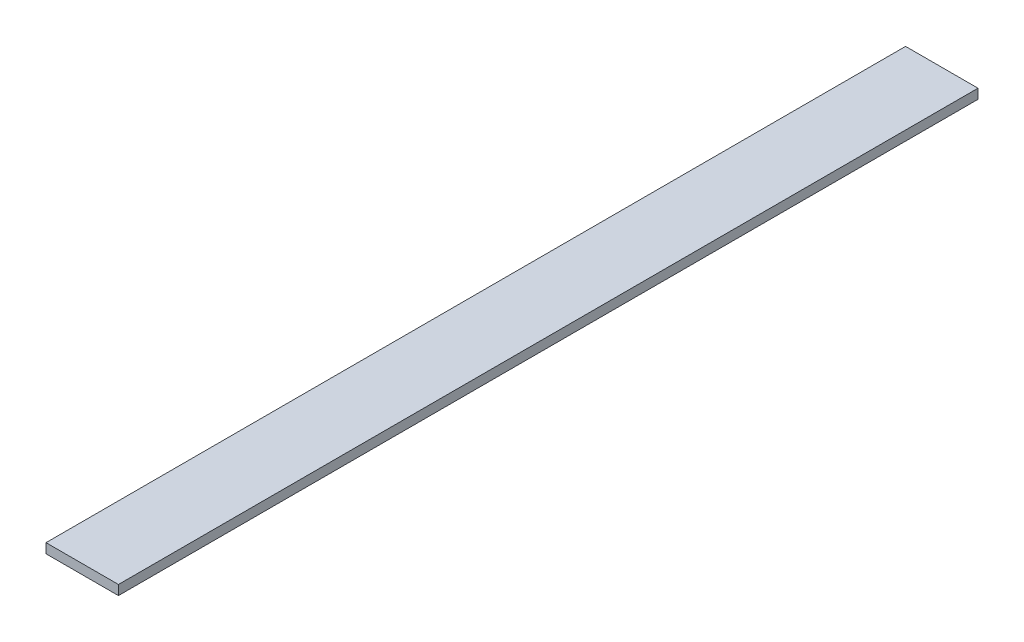
SolidWorks part; units mm, degrees
ref_plane "Front Plane" through (0, 0, 0) normal (0, 0, 1) x (1, 0, 0)
ref_plane "Top Plane" through (0, 0, 0) normal (0, 1, 0) x (1, 0, 0)
ref_plane "Right Plane" through (0, 0, 0) normal (1, 0, 0) x (0, 0, -1)
sketch "Sketch1" plane through (0, 0, 0) normal (0, 0, 1) x (1, 0, 0)
  line L1 (-7.5, 1) -> (7.5, 1)
  line L2 (-7.5, 1) -> (-7.5, -1)
  line L3 (-7.5, -1) -> (7.5, -1)
  line L4 (7.5, 1) -> (7.5, -1)
  line L5 (-7.5, 1) -> (7.5, -1) construction
  line L6 (-7.5, -1) -> (7.5, 1) construction
  point P0 (0, 0)
  dimension "D1" = 15
  dimension "D2" = 2
extrude "Boss-Extrude1" add sketch "Sketch1" along normal blind 178
